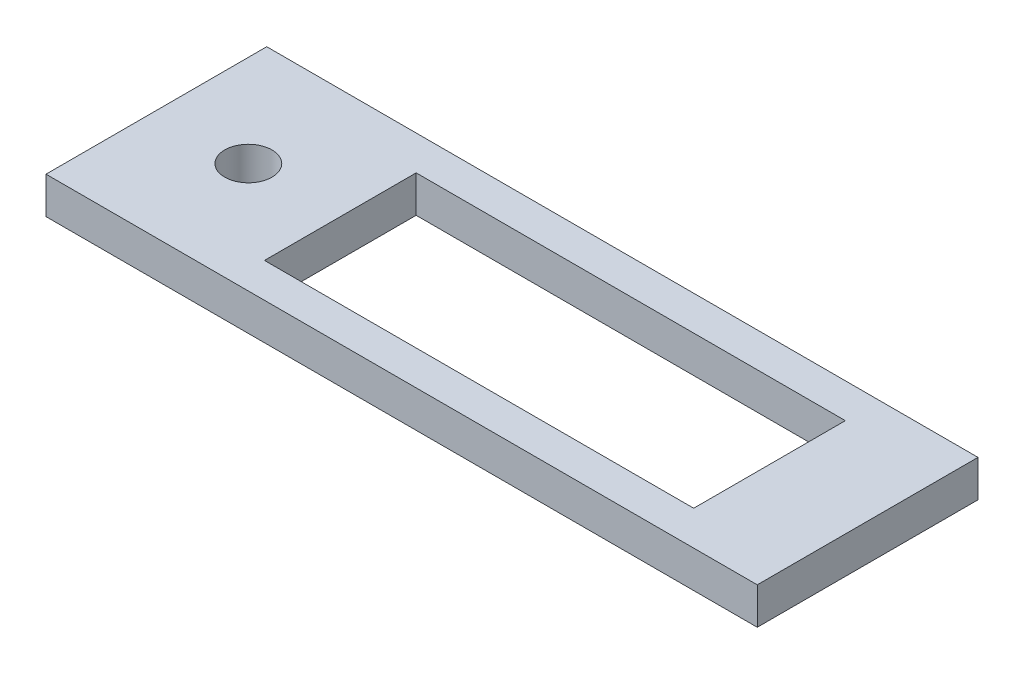
SolidWorks part; units mm, degrees
ref_plane "Front Plane" through (0, 0, 0) normal (0, 0, 1) x (1, 0, 0)
ref_plane "Top Plane" through (0, 0, 0) normal (0, 1, 0) x (1, 0, 0)
ref_plane "Right Plane" through (0, 0, 0) normal (1, 0, 0) x (0, 0, -1)
sketch "Sketch1" plane through (0, 0, 0) normal (0, 1, 0) x (1, 0, 0)
  line L1 (-31.5839, -9) -> (26.4161, -9)
  line L2 (-31.5839, -9) -> (-31.5839, 9)
  line L3 (-31.5839, 9) -> (26.4161, 9)
  line L4 (26.4161, -9) -> (26.4161, 9)
  line L7 (-16.5839, -6.1841) -> (18.4161, -6.1841)
  line L8 (-16.5839, -6.1841) -> (-16.5839, 6.1841)
  line L9 (-16.5839, 6.1841) -> (18.4161, 6.1841)
  line L10 (18.4161, -6.1841) -> (18.4161, 6.1841)
  circle A0 centre (-24.0839, 0) radius 1.9275
  point P0 (0, 0)
  point P8 (0, 0)
  dimension "D1" = 58
  dimension "D2" = 18
  dimension "D3" = 7.5
  dimension "D4" = 35
  dimension "D5" = 7.5
extrude "Boss-Extrude1" add sketch "Sketch1" along normal blind 3
